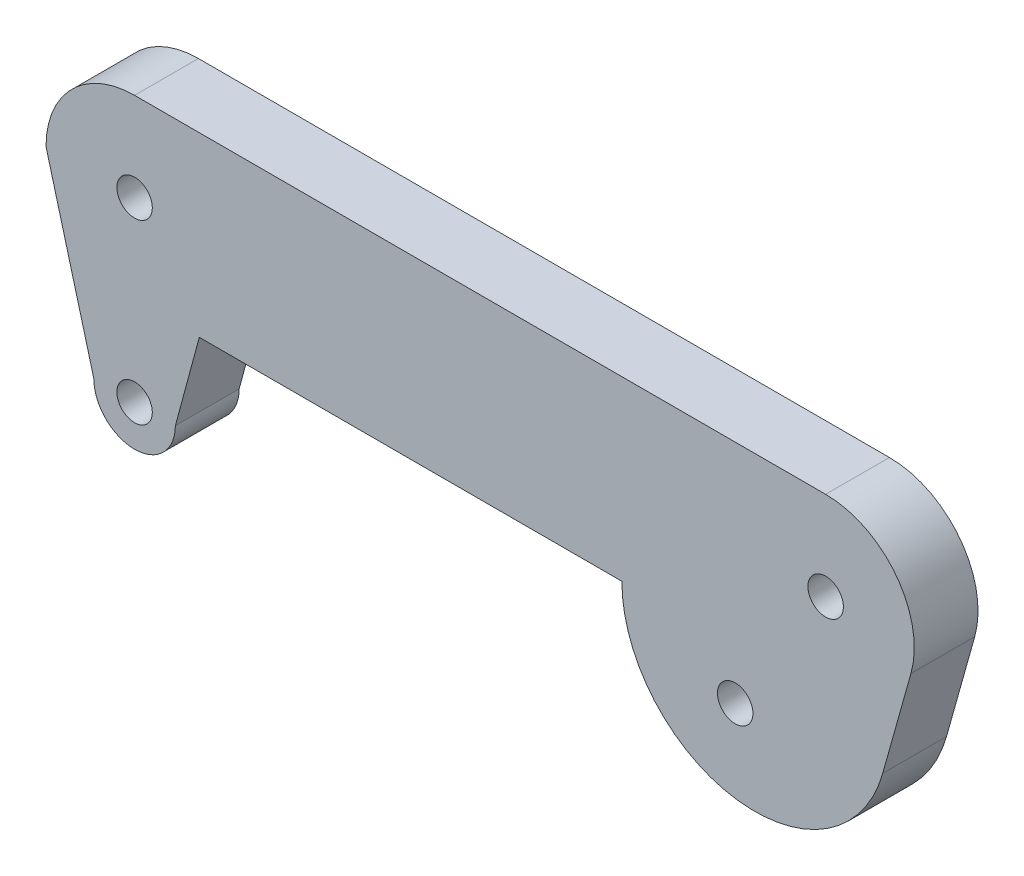
SolidWorks part; units mm, degrees
ref_plane "Front Plane" through (0, 0, 0) normal (0, 0, 1) x (1, 0, 0)
ref_plane "Top Plane" through (0, 0, 0) normal (0, 1, 0) x (1, 0, 0)
ref_plane "Right Plane" through (0, 0, 0) normal (1, 0, 0) x (0, 0, -1)
sketch "Sketch1" plane through (0, 0, 0) normal (0, 0, 1) x (1, 0, 0)
  line L0 (0, 0) -> (39, 0) construction
  line L1 (0, 5) -> (39, 5)
  line L2 (3.6517, -5) -> (27.5, -5)
  line L3 (-5, -0.001) -> (-2.3, -10)
  line L4 (2.3, -10) -> (3.6517, -5)
  line L5 (43.814, -1.3512) -> (42.221, -7.0268)
  arc A0 (0, 5) -> (-5, -0.001) centre (0, 0) ccw
  arc A1 (43.814, -1.3512) -> (39, 5) centre (39, 0) ccw
  arc A2 (-2.3, -10) -> (2.3, -10) centre (0, -10) ccw
  arc A3 (42.221, -7.0268) -> (27.5, -5) centre (35, -5) cw
  circle A4 centre (0, -10) radius 1
  circle A5 centre (0, 0) radius 1
  circle A6 centre (39, 0) radius 1
  circle A7 centre (33.8953, -7.767) radius 1
  point P3 (19.5, 0)
  dimension "D4" = 4.6
  dimension "D5" = 5
  dimension "D10" = 5
  dimension "D12" = 7.5
  dimension "D15" = 2
  dimension "D17" = 7.767
  dimension "D1" = 39
  dimension "D2" = 10
  dimension "D3" = 10
  dimension "D6" = 5
  dimension "D7" = 30.239
  dimension "D8" = 10
  dimension "D9" = 4.8274
  dimension "D11" = 19.5
  dimension "D13" = 35
  dimension "D14" = 5
  dimension "D16" = 33.8953
extrude "Boss-Extrude1" add sketch "Sketch1" along normal blind 3.6
